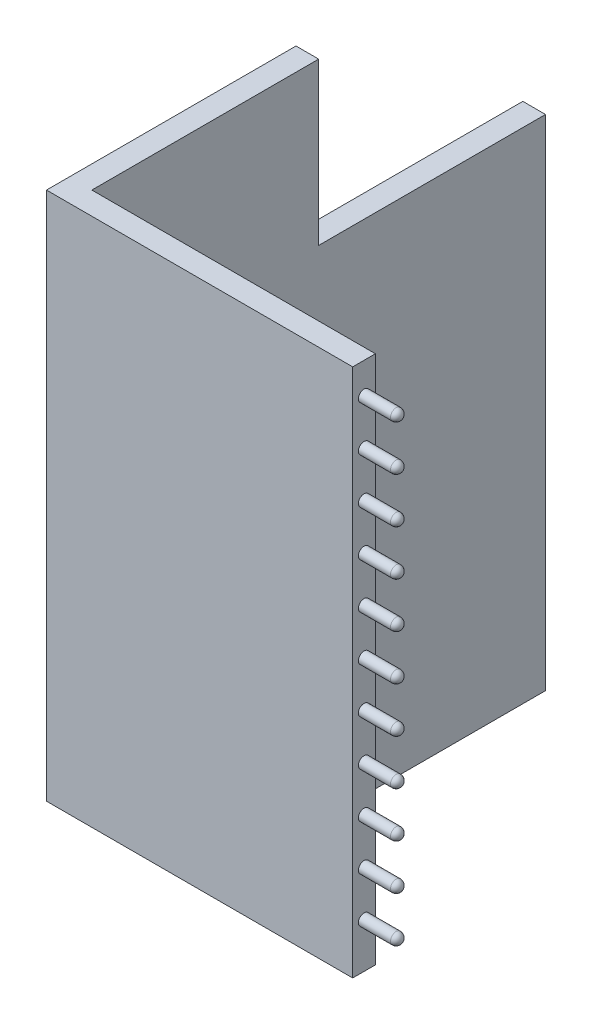
SolidWorks part; units mm, degrees
ref_plane "Alzado" through (0, 0, 0) normal (0, 0, 1) x (1, 0, 0)
ref_plane "Planta" through (0, 0, 0) normal (0, 1, 0) x (1, 0, 0)
ref_plane "Vista lateral" through (0, 0, 0) normal (1, 0, 0) x (0, 0, -1)
sketch "Croquis1" plane through (0, 0, 0) normal (0, 0, 1) x (1, 0, 0)
  line L1 (20.25, 35) -> (-20.25, 35)
  line L2 (20.25, 35) -> (20.25, -35)
  line L3 (20.25, -35) -> (-20.25, -35)
  line L4 (-20.25, 35) -> (-20.25, -35)
  line L5 (20.25, 35) -> (-20.25, -35) construction
  line L6 (20.25, -35) -> (-20.25, 35) construction
  point P0 (0, 0)
  dimension "D1" = 70
  dimension "D2" = 40.5
extrude "Saliente-Extruir1" add sketch "Croquis1" along normal blind 3
sketch "Croquis2" plane through (0, 0, 0) normal (0, 0, -1) x (-1, 0, 0)
  line L0 (20.25, -35) -> (-20.25, -35) construction
  line L1 (20.25, 35) -> (17.25, 35)
  line L2 (20.25, 35) -> (20.25, -35)
  line L3 (20.25, -35) -> (17.25, -35)
  line L4 (17.25, 35) -> (17.25, -35)
  dimension "D1" = 3
extrude "Saliente-Extruir2" add sketch "Croquis2" along normal blind 30
sketch "Croquis3" plane through (20.25, 0, 0) normal (1, 0, 0) x (0, 0, -1)
  line L0 (-1.5, 35) -> (-1.5, -35) construction
  line L1 (-3, 35) -> (0, 35) construction
  line L2 (-3, -35) -> (0, -35) construction
  circle A0 centre (-1.5, 30.9569) radius 0.75
  circle A1 centre (-1.5, 24.9569) radius 0.75
  circle A2 centre (-1.5, 18.9569) radius 0.75
  circle A3 centre (-1.5, 12.9569) radius 0.75
  circle A4 centre (-1.5, 6.9569) radius 0.75
  circle A5 centre (-1.5, 0.9569) radius 0.75
  circle A6 centre (-1.5, -5.0431) radius 0.75
  circle A7 centre (-1.5, -11.0431) radius 0.75
  circle A8 centre (-1.5, -17.0431) radius 0.75
  circle A9 centre (-1.5, -23.0431) radius 0.75
  circle A10 centre (-1.5, -29.0431) radius 0.75
  dimension "D1" = 1.5
  dimension "D2" = 11
extrude "Saliente-Extruir3" add sketch "Croquis3" along normal blind 5
fillet "Redondeo5" radius 0.75 11 edges at (25.25, 31.7069, 1.5) (25.25, -28.2931, 1.5) (25.25, -22.2931, 1.5) (25.25, -16.2931, 1.5) (25.25, -10.2931, 1.5) (25.25, -4.2931, 1.5) (25.25, 1.7069, 1.5) (25.25, 7.7069, 1.5) (25.25, 13.7069, 1.5) (25.25, 19.7069, 1.5) (25.25, 25.7069, 1.5)
sketch "Croquis4" plane through (-17.25, 0, 0) normal (1, 0, 0) x (0, 0, -1)
  line L0 (30, 35) -> (30, -35) construction
  line L1 (30, 13.66) -> (60, 13.66)
  line L2 (30, 13.66) -> (30, -52.34)
  line L3 (30, -52.34) -> (60, -52.34)
  line L4 (60, 13.66) -> (60, -52.34)
  line L5 (30, -35) -> (0, -35) construction
  dimension "D1" = 66
  dimension "D2" = 17.34
  dimension "D3" = 30
extrude "Saliente-Extruir5" add sketch "Croquis4" against normal blind 3
